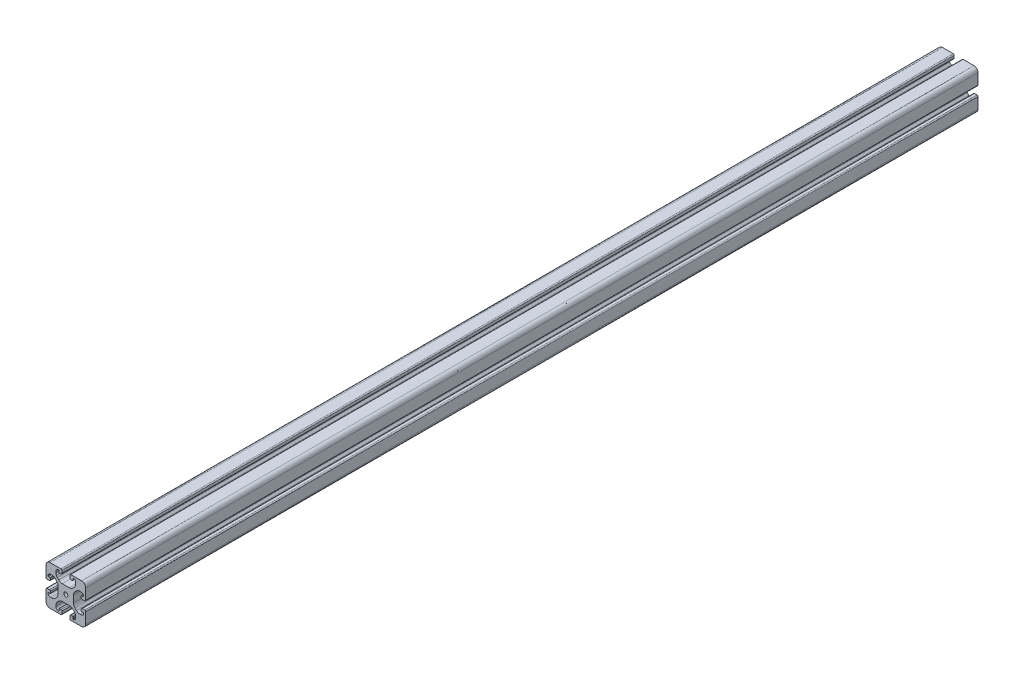
SolidWorks part; units mm, degrees
material "氧化铝"
ref_plane "前视基准面" through (0, 0, 0) normal (0, 0, 1) x (1, 0, 0)
ref_plane "上视基准面" through (0, 0, 0) normal (0, 1, 0) x (1, 0, 0)
ref_plane "右视基准面" through (0, 0, 0) normal (1, 0, 0) x (0, 0, -1)
sketch "Model" plane through (0, 0, 0) normal (0, 0, 1) x (1, 0, 0)
  line L2 (3038.626, 1538.5549) -> (3045.7412, 1538.5549)
  line L3 (3037.1836, 1526.3047) -> (3026.1835, 1526.3048)
  line L4 (3032.1835, 1530.8048) -> (3032.1835, 1532.1123)
  line L5 (3033.6481, 1535.6478) -> (3035.0903, 1537.0902)
  line L6 (3034.7336, 1528.3048) -> (3034.6836, 1528.3048)
  line L7 (3037.1836, 1530.8048) -> (3035.6835, 1530.8048)
  line L8 (3035.1835, 1528.7549) -> (3035.1835, 1530.3049)
  line L9 (3022.1835, 1530.305) -> (3022.1835, 1541.3049)
  line L10 (3038.1835, 1565.3049) -> (3038.1835, 1562.8049)
  line L11 (3031.5267, 1554.8404) -> (3032.9691, 1553.398)
  line L12 (3026.6837, 1556.305) -> (3027.9911, 1556.305)
  line L13 (3026.1835, 1553.305) -> (3024.6335, 1553.305)
  line L14 (3024.1836, 1553.7549) -> (3024.1836, 1553.8049)
  line L15 (3026.6837, 1551.3049) -> (3026.6837, 1552.805)
  line L16 (3023.1837, 1550.305) -> (3025.6835, 1550.305)
  line L17 (3022.1835, 1562.3048) -> (3022.1835, 1551.3049)
  line L18 (3023.1837, 1542.3048) -> (3025.6835, 1542.3048)
  line L19 (3026.6837, 1541.3049) -> (3026.6837, 1539.8048)
  line L20 (3024.1836, 1538.8549) -> (3024.1836, 1538.8048)
  line L21 (3026.1835, 1539.3048) -> (3024.6335, 1539.3048)
  line L22 (3026.6837, 1536.3048) -> (3027.9911, 1536.3048)
  line L23 (3031.5267, 1537.7694) -> (3032.9691, 1539.2118)
  line L24 (3035.1835, 1563.8549) -> (3035.1835, 1562.3049)
  line L25 (3037.1836, 1561.805) -> (3035.6835, 1561.805)
  line L26 (3034.7336, 1564.305) -> (3034.6836, 1564.305)
  line L27 (3038.1835, 1527.3048) -> (3038.1835, 1529.8049)
  line L28 (3049.9338, 1549.8624) -> (3049.9338, 1542.7473)
  line L29 (3047.1836, 1566.3051) -> (3058.1838, 1566.305)
  line L30 (3052.1837, 1561.805) -> (3052.1837, 1560.4975)
  line L31 (3050.7191, 1556.962) -> (3049.2769, 1555.5195)
  line L32 (3033.6481, 1556.962) -> (3035.0903, 1555.5195)
  line L33 (3032.1835, 1561.805) -> (3032.1835, 1560.4975)
  line L34 (3046.1837, 1527.3048) -> (3046.1837, 1529.8049)
  line L35 (3049.6336, 1564.305) -> (3049.6837, 1564.305)
  line L36 (3047.1836, 1561.805) -> (3048.6837, 1561.805)
  line L37 (3049.1837, 1563.8549) -> (3049.1837, 1562.3049)
  line L38 (3052.8406, 1537.7694) -> (3051.3981, 1539.2118)
  line L39 (3057.6836, 1536.3048) -> (3056.3761, 1536.3048)
  line L40 (3058.1838, 1539.3048) -> (3059.7337, 1539.3048)
  line L41 (3060.1836, 1538.8549) -> (3060.1836, 1538.8048)
  line L42 (3057.6836, 1541.3049) -> (3057.6836, 1539.8048)
  line L43 (3061.1835, 1542.3048) -> (3058.6837, 1542.3048)
  line L44 (3037.1836, 1566.3051) -> (3026.1835, 1566.305)
  line L45 (3062.1837, 1562.3048) -> (3062.1837, 1551.3049)
  line L46 (3038.626, 1554.0549) -> (3045.7412, 1554.0549)
  line L47 (3061.1835, 1550.305) -> (3058.6837, 1550.305)
  line L48 (3057.6836, 1551.3049) -> (3057.6836, 1552.805)
  line L49 (3060.1836, 1553.7549) -> (3060.1836, 1553.8049)
  line L50 (3058.1838, 1553.305) -> (3059.7337, 1553.305)
  line L51 (3057.6836, 1556.305) -> (3056.3761, 1556.305)
  line L52 (3034.4335, 1549.8624) -> (3034.4335, 1542.7473)
  line L53 (3052.8406, 1554.8404) -> (3051.3981, 1553.398)
  line L54 (3046.1837, 1565.3049) -> (3046.1837, 1562.8049)
  line L55 (3062.1837, 1530.305) -> (3062.1837, 1541.3049)
  line L56 (3049.1837, 1528.7549) -> (3049.1837, 1530.3049)
  line L57 (3047.1836, 1530.8048) -> (3048.6837, 1530.8048)
  line L58 (3049.6336, 1528.3048) -> (3049.6837, 1528.3048)
  line L59 (3050.7191, 1535.6478) -> (3049.2769, 1537.0902)
  line L60 (3052.1837, 1530.8048) -> (3052.1837, 1532.1123)
  line L61 (3047.1836, 1526.3047) -> (3058.1838, 1526.3048)
  spline S0 degree 3 poles (3026.1835, 1526.3048) (3024.8345, 1526.3048) (3023.0907, 1527.3653) (3022.1835, 1529.3623) (3022.1835, 1530.305) knots 0 0 0 0 0.550544 1 1 1 1
  spline S1 degree 3 poles (3032.1835, 1532.1123) (3032.1835, 1532.8016) (3032.4749, 1534.0839) (3033.1746, 1535.1743) (3033.6481, 1535.6478) knots 0 0 0 0 0.510204 1 1 1 1
  spline S2 degree 3 poles (3035.0903, 1537.0902) (3035.5565, 1537.5565) (3036.6626, 1538.2661) (3037.9261, 1538.5549) (3038.626, 1538.5549) knots 0 0 0 0 0.489373 1 1 1 1
  spline S3 degree 3 poles (3038.1835, 1529.8049) (3038.1835, 1530.1088) (3037.8896, 1530.5989) (3037.4374, 1530.8048) (3037.1836, 1530.8048) knots 0 0 0 0 0.565195 1 1 1 1
  spline S4 degree 3 poles (3035.6835, 1530.8048) (3035.5526, 1530.8048) (3035.3033, 1530.6873) (3035.1835, 1530.4632) (3035.1835, 1530.3049) knots 0 0 0 0 0.482406 1 1 1 1
  spline S5 degree 3 poles (3035.1835, 1528.7549) (3035.1835, 1528.6211) (3035.0566, 1528.3999) (3034.8531, 1528.3048) (3034.7336, 1528.3048) knots 0 0 0 0 0.549542 1 1 1 1
  spline S6 degree 3 poles (3034.6836, 1528.3048) (3033.9863, 1528.3048) (3032.7434, 1528.9085) (3032.1835, 1530.0457) (3032.1835, 1530.8048) knots 0 0 0 0 0.502794 1 1 1 1
  spline S7 degree 3 poles (3022.1835, 1541.3049) (3022.1835, 1541.6421) (3022.4486, 1542.0781) (3022.9479, 1542.3048) (3023.1837, 1542.3048) knots 0 0 0 0 0.550415 1 1 1 1
  spline S8 degree 3 poles (3025.6835, 1542.3048) (3026.0194, 1542.3048) (3026.4561, 1542.0413) (3026.6837, 1541.5421) (3026.6837, 1541.3049) knots 0 0 0 0 0.548464 1 1 1 1
  spline S9 degree 3 poles (3026.6837, 1539.8048) (3026.6837, 1539.6386) (3026.5536, 1539.4195) (3026.3039, 1539.3048) (3026.1835, 1539.3048) knots 0 0 0 0 0.543008 1 1 1 1
  spline S10 degree 3 poles (3024.6335, 1539.3048) (3024.4666, 1539.3048) (3024.2778, 1539.1702) (3024.1836, 1538.9461) (3024.1836, 1538.8549) knots 0 0 0 0 0.601272 1 1 1 1
  spline S11 degree 3 poles (3024.1836, 1538.8048) (3024.1836, 1537.973) (3024.8335, 1536.8769) (3026.0817, 1536.3048) (3026.6837, 1536.3048) knots 0 0 0 0 0.543506 1 1 1 1
  spline S12 degree 3 poles (3027.9911, 1536.3048) (3028.6698, 1536.3048) (3029.9377, 1536.5775) (3031.0429, 1537.2857) (3031.5267, 1537.7694) knots 0 0 0 0 0.495307 1 1 1 1
  spline S13 degree 3 poles (3032.9691, 1539.2118) (3033.4334, 1539.6761) (3034.1274, 1540.7681) (3034.4335, 1542.0508) (3034.4335, 1542.7473) knots 0 0 0 0 0.481772 1 1 1 1
  spline S14 degree 3 poles (3037.1836, 1526.3047) (3037.4, 1526.3047) (3037.8987, 1526.5226) (3038.1835, 1526.9491) (3038.1835, 1527.3048) knots 0 0 0 0 0.421049 1 1 1 1
  spline S15 degree 3 poles (3058.1838, 1566.305) (3059.5327, 1566.305) (3061.2765, 1565.2445) (3062.1837, 1563.2474) (3062.1837, 1562.3048) knots 0 0 0 0 0.550544 1 1 1 1
  spline S16 degree 3 poles (3052.1837, 1560.4975) (3052.1837, 1559.8082) (3051.8923, 1558.5259) (3051.1926, 1557.4355) (3050.7191, 1556.962) knots 0 0 0 0 0.510204 1 1 1 1
  spline S17 degree 3 poles (3049.2769, 1555.5195) (3048.8108, 1555.0533) (3047.7046, 1554.3437) (3046.4411, 1554.0549) (3045.7412, 1554.0549) knots 0 0 0 0 0.489373 1 1 1 1
  spline S18 degree 3 poles (3046.1837, 1562.8049) (3046.1837, 1562.501) (3046.4776, 1562.0109) (3046.9298, 1561.805) (3047.1836, 1561.805) knots 0 0 0 0 0.565195 1 1 1 1
  spline S19 degree 3 poles (3037.1836, 1566.3051) (3037.4, 1566.3051) (3037.8987, 1566.0872) (3038.1835, 1565.6607) (3038.1835, 1565.3049) knots 0 0 0 0 0.421049 1 1 1 1
  spline S20 degree 3 poles (3048.6837, 1561.805) (3048.8146, 1561.805) (3049.0639, 1561.9225) (3049.1837, 1562.1466) (3049.1837, 1562.3049) knots 0 0 0 0 0.482406 1 1 1 1
  spline S21 degree 3 poles (3032.9691, 1553.398) (3033.4334, 1552.9336) (3034.1274, 1551.8416) (3034.4335, 1550.559) (3034.4335, 1549.8624) knots 0 0 0 0 0.481772 1 1 1 1
  spline S22 degree 3 poles (3027.9911, 1556.305) (3028.6698, 1556.305) (3029.9377, 1556.0322) (3031.0429, 1555.3241) (3031.5267, 1554.8404) knots 0 0 0 0 0.495307 1 1 1 1
  spline S23 degree 3 poles (3024.1836, 1553.8049) (3024.1836, 1554.6368) (3024.8335, 1555.7328) (3026.0817, 1556.305) (3026.6837, 1556.305) knots 0 0 0 0 0.543506 1 1 1 1
  spline S24 degree 3 poles (3024.6335, 1553.305) (3024.4666, 1553.305) (3024.2778, 1553.4396) (3024.1836, 1553.6637) (3024.1836, 1553.7549) knots 0 0 0 0 0.601272 1 1 1 1
  spline S25 degree 3 poles (3026.6837, 1552.805) (3026.6837, 1552.9712) (3026.5536, 1553.1903) (3026.3039, 1553.305) (3026.1835, 1553.305) knots 0 0 0 0 0.543008 1 1 1 1
  spline S26 degree 3 poles (3025.6835, 1550.305) (3026.0194, 1550.305) (3026.4561, 1550.5685) (3026.6837, 1551.0677) (3026.6837, 1551.3049) knots 0 0 0 0 0.548464 1 1 1 1
  spline S27 degree 3 poles (3022.1835, 1551.3049) (3022.1835, 1550.9677) (3022.4486, 1550.5317) (3022.9479, 1550.305) (3023.1837, 1550.305) knots 0 0 0 0 0.550415 1 1 1 1
  spline S28 degree 3 poles (3049.1837, 1563.8549) (3049.1837, 1563.9886) (3049.3106, 1564.2099) (3049.5141, 1564.305) (3049.6336, 1564.305) knots 0 0 0 0 0.549542 1 1 1 1
  spline S29 degree 3 poles (3049.6837, 1564.305) (3050.3809, 1564.305) (3051.6238, 1563.7012) (3052.1837, 1562.5641) (3052.1837, 1561.805) knots 0 0 0 0 0.502794 1 1 1 1
  spline S30 degree 3 poles (3062.1837, 1551.3049) (3062.1837, 1550.9677) (3061.9186, 1550.5317) (3061.4193, 1550.305) (3061.1835, 1550.305) knots 0 0 0 0 0.550415 1 1 1 1
  spline S31 degree 3 poles (3058.6837, 1550.305) (3058.3478, 1550.305) (3057.9111, 1550.5685) (3057.6836, 1551.0677) (3057.6836, 1551.3049) knots 0 0 0 0 0.548464 1 1 1 1
  spline S32 degree 3 poles (3057.6836, 1552.805) (3057.6836, 1552.9712) (3057.8136, 1553.1903) (3058.0633, 1553.305) (3058.1838, 1553.305) knots 0 0 0 0 0.543008 1 1 1 1
  spline S33 degree 3 poles (3059.7337, 1553.305) (3059.9006, 1553.305) (3060.0894, 1553.4396) (3060.1836, 1553.6637) (3060.1836, 1553.7549) knots 0 0 0 0 0.601272 1 1 1 1
  spline S34 degree 3 poles (3060.1836, 1553.8049) (3060.1836, 1554.6368) (3059.5337, 1555.7328) (3058.2856, 1556.305) (3057.6836, 1556.305) knots 0 0 0 0 0.543506 1 1 1 1
  spline S35 degree 3 poles (3056.3761, 1556.305) (3055.6974, 1556.305) (3054.4295, 1556.0322) (3053.3243, 1555.3241) (3052.8406, 1554.8404) knots 0 0 0 0 0.495307 1 1 1 1
  spline S36 degree 3 poles (3051.3981, 1553.398) (3050.9338, 1552.9336) (3050.2398, 1551.8416) (3049.9338, 1550.559) (3049.9338, 1549.8624) knots 0 0 0 0 0.481772 1 1 1 1
  spline S37 degree 3 poles (3047.1836, 1566.3051) (3046.9672, 1566.3051) (3046.4685, 1566.0872) (3046.1837, 1565.6607) (3046.1837, 1565.3049) knots 0 0 0 0 0.421049 1 1 1 1
  spline S38 degree 3 poles (3034.6836, 1564.305) (3033.9863, 1564.305) (3032.7434, 1563.7012) (3032.1835, 1562.5641) (3032.1835, 1561.805) knots 0 0 0 0 0.502794 1 1 1 1
  spline S39 degree 3 poles (3035.1835, 1563.8549) (3035.1835, 1563.9886) (3035.0566, 1564.2099) (3034.8531, 1564.305) (3034.7336, 1564.305) knots 0 0 0 0 0.549542 1 1 1 1
  spline S40 degree 3 poles (3035.6835, 1561.805) (3035.5526, 1561.805) (3035.3033, 1561.9225) (3035.1835, 1562.1466) (3035.1835, 1562.3049) knots 0 0 0 0 0.482406 1 1 1 1
  spline S41 degree 3 poles (3038.1835, 1562.8049) (3038.1835, 1562.501) (3037.8896, 1562.0109) (3037.4374, 1561.805) (3037.1836, 1561.805) knots 0 0 0 0 0.565195 1 1 1 1
  spline S42 degree 3 poles (3047.1836, 1526.3047) (3046.9672, 1526.3047) (3046.4685, 1526.5226) (3046.1837, 1526.9491) (3046.1837, 1527.3048) knots 0 0 0 0 0.421049 1 1 1 1
  spline S43 degree 3 poles (3051.3981, 1539.2118) (3050.9338, 1539.6761) (3050.2398, 1540.7681) (3049.9338, 1542.0508) (3049.9338, 1542.7473) knots 0 0 0 0 0.481772 1 1 1 1
  spline S44 degree 3 poles (3056.3761, 1536.3048) (3055.6974, 1536.3048) (3054.4295, 1536.5775) (3053.3243, 1537.2857) (3052.8406, 1537.7694) knots 0 0 0 0 0.495307 1 1 1 1
  spline S45 degree 3 poles (3060.1836, 1538.8048) (3060.1836, 1537.973) (3059.5337, 1536.8769) (3058.2856, 1536.3048) (3057.6836, 1536.3048) knots 0 0 0 0 0.543506 1 1 1 1
  spline S46 degree 3 poles (3059.7337, 1539.3048) (3059.9006, 1539.3048) (3060.0894, 1539.1702) (3060.1836, 1538.9461) (3060.1836, 1538.8549) knots 0 0 0 0 0.601272 1 1 1 1
  spline S47 degree 3 poles (3057.6836, 1539.8048) (3057.6836, 1539.6386) (3057.8136, 1539.4195) (3058.0633, 1539.3048) (3058.1838, 1539.3048) knots 0 0 0 0 0.543008 1 1 1 1
  spline S48 degree 3 poles (3058.6837, 1542.3048) (3058.3478, 1542.3048) (3057.9111, 1542.0413) (3057.6836, 1541.5421) (3057.6836, 1541.3049) knots 0 0 0 0 0.548464 1 1 1 1
  spline S49 degree 3 poles (3062.1837, 1541.3049) (3062.1837, 1541.6421) (3061.9186, 1542.0781) (3061.4193, 1542.3048) (3061.1835, 1542.3048) knots 0 0 0 0 0.550415 1 1 1 1
  spline S50 degree 3 poles (3049.6837, 1528.3048) (3050.3809, 1528.3048) (3051.6238, 1528.9085) (3052.1837, 1530.0457) (3052.1837, 1530.8048) knots 0 0 0 0 0.502794 1 1 1 1
  spline S51 degree 3 poles (3035.0903, 1555.5195) (3035.5565, 1555.0533) (3036.6626, 1554.3437) (3037.9261, 1554.0549) (3038.626, 1554.0549) knots 0 0 0 0 0.489373 1 1 1 1
  spline S52 degree 3 poles (3032.1835, 1560.4975) (3032.1835, 1559.8082) (3032.4749, 1558.5259) (3033.1746, 1557.4355) (3033.6481, 1556.962) knots 0 0 0 0 0.510204 1 1 1 1
  spline S53 degree 3 poles (3049.1837, 1528.7549) (3049.1837, 1528.6211) (3049.3106, 1528.3999) (3049.5141, 1528.3048) (3049.6336, 1528.3048) knots 0 0 0 0 0.549542 1 1 1 1
  spline S54 degree 3 poles (3048.6837, 1530.8048) (3048.8146, 1530.8048) (3049.0639, 1530.6873) (3049.1837, 1530.4632) (3049.1837, 1530.3049) knots 0 0 0 0 0.482406 1 1 1 1
  spline S55 degree 3 poles (3046.1837, 1529.8049) (3046.1837, 1530.1088) (3046.4776, 1530.5989) (3046.9298, 1530.8048) (3047.1836, 1530.8048) knots 0 0 0 0 0.565195 1 1 1 1
  spline S56 degree 3 poles (3049.2769, 1537.0902) (3048.8108, 1537.5565) (3047.7046, 1538.2661) (3046.4411, 1538.5549) (3045.7412, 1538.5549) knots 0 0 0 0 0.489373 1 1 1 1
  spline S57 degree 3 poles (3052.1837, 1532.1123) (3052.1837, 1532.8016) (3051.8923, 1534.0839) (3051.1926, 1535.1743) (3050.7191, 1535.6478) knots 0 0 0 0 0.510204 1 1 1 1
  spline S58 degree 3 poles (3058.1838, 1526.3048) (3059.5327, 1526.3048) (3061.2765, 1527.3653) (3062.1837, 1529.3623) (3062.1837, 1530.305) knots 0 0 0 0 0.550544 1 1 1 1
  spline S68 degree 3 poles (3026.1835, 1566.305) (3024.8345, 1566.305) (3023.0907, 1565.2445) (3022.1835, 1563.2474) (3022.1835, 1562.3048) knots 0 0 0 0 0.550544 1 1 1 1
extrude "凸台-拉伸3" add sketch "Model" along normal blind 900 contours S22 L11 S21 L52 S13 L23 S12 L22 S11 L20 S10 L21 S9 L19 S8 L18 S7 L9 S0 L3 S14 L27 S3 L7 S4 L8 S5 L6 S6 L4 S1 L5 S2 L2 S56 L59 S57 L60 S50 L58 S53 L56 S54 L57 S55 L34 S42 L61 S58 L55 S49 L43 S48 L42 S47 L40 S46 L41 S45 L39 S44 L38 S43 L28 S36 L53 S35 L51 S34 L49 S33 L50 S32 L48 S31 L47 S30 L45 S15 L29 S37 L54 S18 L36 S20 L37 S28 L35 S29 L30 S16 L31 S17 L46 S51 L32 S52 L33 S38 L26 S39 L24 S40 L25 S41 L10 S19 L44 S68 L17 S27 L16 S26 L15 S25 L13 S24 L14 S23 L12
sketch "草图1" plane through (0, 0, 900) normal (0, 0, 1) x (1, 0, 0)
  point P0 (3042.1836, 1546.3049)
hole_wizard "M5 螺纹孔1" positions "草图2" profile "草图3" tap size "M5" standard "GB"
sketch "草图2" plane through (0, 0, 900) normal (0, 0, 1) x (1, 0, 0)
  point P0 (3042.1836, 1546.3049)
sketch "草图3" plane through (3042.1836, 1546.3049, 900) normal (1, 0, 0) x (0, -1, 0)
  line L0 (0, 0) -> (0, 15.2618)
  line L1 (0, 15.2618) -> (2.1, 14)
  line L2 (2.1, 14) -> (2.1, 0)
  line L5 (2.1, 0) -> (0, 0)
  line L10 (0, 15.2618) -> (-2.1, 14) construction
  line L11 (0, -6.35) -> (0, 107.95) construction
  dimension "螺纹孔钻头直径" = 4.2
  dimension "螺纹孔钻头深度" = 14
  dimension "导头角度" = 118
cosmetic thread "孔螺蚊线1" parameters "D1"=10, "D2"=5
sketch "草图4" plane through (0, 0, 0) normal (0, 0, -1) x (-1, 0, 0)
  point P0 (-3042.1836, 1546.3049)
hole_wizard "M5 螺纹孔2" positions "草图5" profile "草图6" tap size "M5" standard "GB"
sketch "草图5" plane through (0, 0, 0) normal (0, 0, -1) x (-1, 0, 0)
  point P0 (-3042.1836, 1546.3049)
sketch "草图6" plane through (3042.1836, 1546.3049, 0) normal (1, 0, 0) x (0, 1, 0)
  line L0 (0, 0) -> (0, 15.2618)
  line L1 (0, 15.2618) -> (2.1, 14)
  line L2 (2.1, 14) -> (2.1, 0)
  line L5 (2.1, 0) -> (0, 0)
  line L10 (0, 15.2618) -> (-2.1, 14) construction
  line L11 (0, -6.35) -> (0, 107.95) construction
  dimension "螺纹孔钻头直径" = 4.2
  dimension "螺纹孔钻头深度" = 14
  dimension "导头角度" = 118
cosmetic thread "孔螺蚊线2" parameters "D1"=10, "D2"=5
sketch "草图7" plane through (3049.9338, 0, 0) normal (1, 0, 0) x (0, 0, -1)
  line L0 (-900, 1549.8624) -> (-900, 1542.7473) construction
  point P0 (-450, 1546.3049)
  dimension "D1" = 450
hole_wizard "M5 螺纹孔3" positions "草图8" profile "草图9" tap size "M5" standard "GB" end condition through all
sketch "草图8" plane through (3049.9338, 0, 0) normal (1, 0, 0) x (0, 0, -1)
  point P0 (-450, 1546.3049)
cosmetic thread "孔螺蚊线3" parameters "D2"=5
sketch "草图9" plane through (3049.9338, 1546.3049, 450) normal (0, 1, 0) x (0, 0, -1)
  line L0 (0, 0) -> (0, 27.7503)
  line L1 (0, 27.7503) -> (2.1, 27.7503)
  line L2 (2.1, 27.7503) -> (2.1, 0)
  line L5 (2.1, 0) -> (0, 0)
  line L11 (0, -6.35) -> (0, 107.95) construction
  dimension "通孔螺纹孔钻头直径" = 4.2
  dimension "通孔螺纹孔钻头深度" = 27.7503
sketch "草图10" plane through (0, 1554.0549, 0) normal (0, 1, 0) x (1, 0, 0)
  line L0 (3038.626, 0) -> (3045.7412, 0) construction
  point P0 (3042.1836, -450)
  dimension "D1" = 450
hole_wizard "M5 螺纹孔4" positions "草图11" profile "草图12" tap size "M5" standard "GB" end condition through all
sketch "草图11" plane through (0, 1554.0549, 0) normal (0, 1, 0) x (1, 0, 0)
  point P0 (3042.1836, -450)
sketch "草图12" plane through (3042.1836, 1554.0549, 450) normal (1, 0, 0) x (0, 0, 1)
  line L0 (0, 0) -> (0, 27.7503)
  line L1 (0, 27.7503) -> (2.1, 27.7503)
  line L2 (2.1, 27.7503) -> (2.1, 0)
  line L5 (2.1, 0) -> (0, 0)
  line L11 (0, -6.35) -> (0, 107.95) construction
  dimension "通孔螺纹孔钻头直径" = 4.2
  dimension "通孔螺纹孔钻头深度" = 27.7503
cosmetic thread "孔螺蚊线4" parameters "D2"=5
